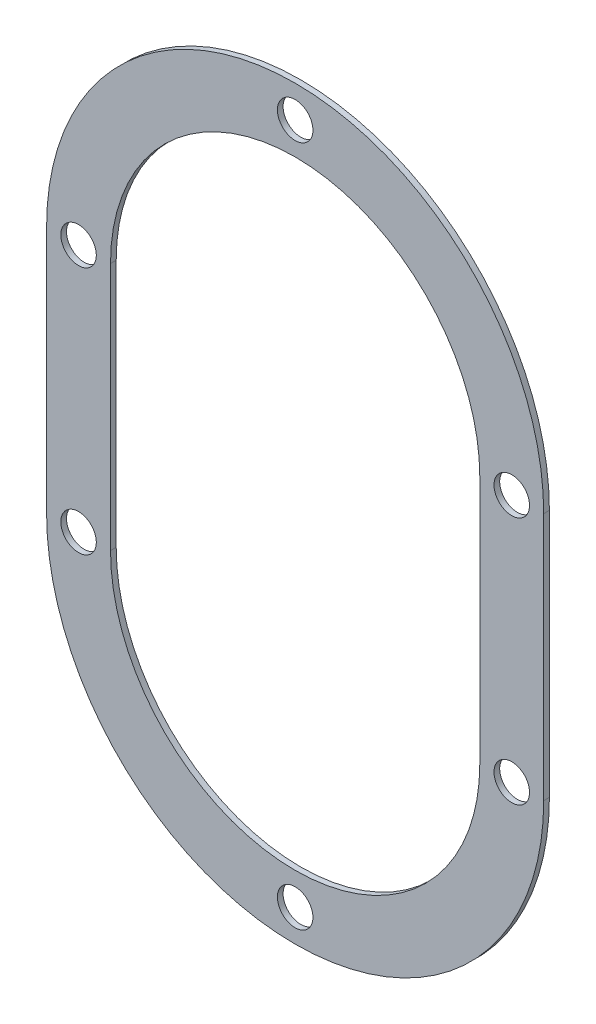
SolidWorks part; units mm, degrees
ref_plane "Front Plane" through (0, 0, 0) normal (0, 0, 1) x (1, 0, 0)
ref_plane "Top Plane" through (0, 0, 0) normal (0, 1, 0) x (1, 0, 0)
ref_plane "Right Plane" through (0, 0, 0) normal (1, 0, 0) x (0, 0, -1)
sketch "Sketch1" plane through (0, 0, 0) normal (0, 0, 1) x (1, 0, 0)
  line L0 (-35, 0) -> (-35, -35)
  line L1 (35, 0) -> (35, -35)
  line L2 (-26, 0) -> (-26, -35)
  line L3 (26, 0) -> (26, -35)
  line L4 (0, 35) -> (0, 26) construction
  line L5 (0, 26) -> (0, -61) construction
  line L6 (0, -61) -> (0, -70) construction
  line L7 (-35, 0) -> (-26, 0) construction
  line L8 (26, 0) -> (35, 0) construction
  line L9 (-35, -35) -> (-26, -35) construction
  line L10 (26, -35) -> (35, -35) construction
  arc A0 (35, 0) -> (-35, 0) centre (0, 0) ccw
  arc A1 (-35, -35) -> (35, -35) centre (0, -35) ccw
  arc A2 (26, 0) -> (-26, 0) centre (0, 0) ccw
  arc A3 (-26, -35) -> (26, -35) centre (0, -35) ccw
  circle A4 centre (0, 0) radius 30.5 construction
  circle A5 centre (0, -35) radius 30.5 construction
  circle A6 centre (-30.5, 0) radius 2.5
  circle A7 centre (0, 30.5) radius 2.5
  circle A8 centre (30.5, 0) radius 2.5
  circle A9 centre (0, -65.5) radius 2.5
  circle A10 centre (-30.5, -35) radius 2.5
  circle A11 centre (30.5, -35) radius 2.5
  point P15 (-30.5, 0)
  point P18 (-30.5, -35)
  dimension "D2" = 70
  dimension "D4" = 5
  dimension "D1" = 35
  dimension "D3" = 9
extrude "Boss-Extrude1" add sketch "Sketch1" along normal blind 0.8
